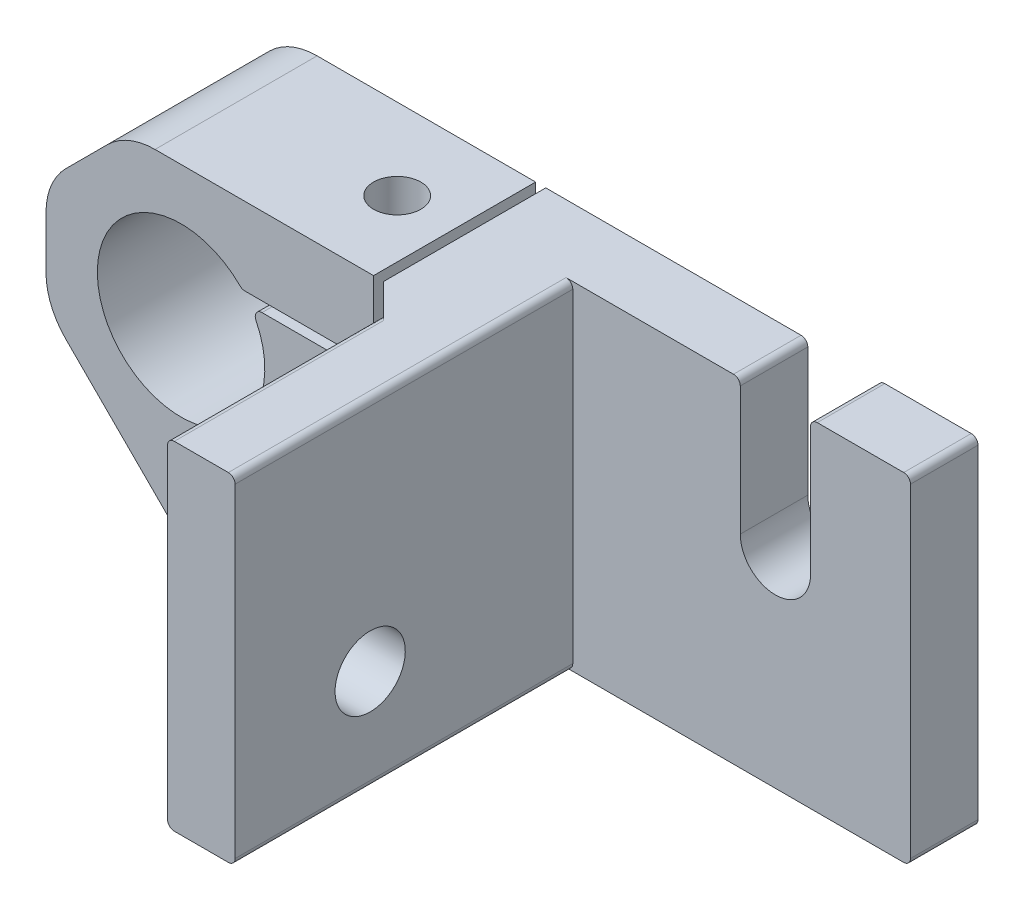
SolidWorks part; units mm, degrees
ref_plane "XY" through (0, 0, 0) normal (0, 0, 1) x (1, 0, 0)
ref_plane "XZ" through (0, 0, 0) normal (0, 1, 0) x (1, 0, 0)
ref_plane "YZ" through (0, 0, 0) normal (1, 0, 0) x (0, 0, -1)
sketch "Sketch1" plane through (0, 0, 0) normal (0, 0, 1) x (1, 0, 0)
  line L0 (-22.5, 12.5) -> (-28.5, 6.5)
  line L1 (-28.5, -12.5) -> (-17.5, -12.5) construction
  line L2 (-28.5, -12.5) -> (-28.5, -1.5) construction
  line L3 (-28.5, 12.5) -> (-5.7, 12.5) construction
  line L4 (28.5, -12.5) -> (28.5, 12.5)
  line L5 (-28.5, -12.5) -> (28.5, 12.5) construction
  line L6 (-28.5, 12.5) -> (28.5, -12.5) construction
  line L7 (28.5, -12.5) -> (-28.5, -12.5) construction
  line L8 (28.5, -12.5) -> (28.5, 12.5) construction
  line L9 (28.5, 12.5) -> (-28.5, 12.5) construction
  line L10 (-28.5, -12.5) -> (-28.5, 12.5) construction
  line L11 (28.5, -12.5) -> (-28.5, 12.5) construction
  line L12 (28.5, 12.5) -> (-28.5, -12.5) construction
  line L13 (-13.9859, 6.75) -> (-4.25, 6.75)
  line L14 (-28.5, 6.5) -> (-28.5, 12.5) construction
  line L15 (-17.5, -12.5) -> (-28.5, -1.5)
  line L16 (-5.7, 12.5) -> (-4.25, 12.5)
  line L17 (-28.5, 6.5) -> (-28.5, 12.5) construction
  line L18 (-28.5, -1.5) -> (-28.5, 6.5)
  line L19 (-17.5, -12.5) -> (28.5, -12.5)
  line L20 (-4.25, 6.75) -> (-4.25, 12.5)
  line L21 (-13.3824, 6) -> (-3.5, 6)
  line L22 (-3.5, 6) -> (-3.5, 12.5)
  line L23 (-13.9859, 6) -> (-3.5, 6) construction
  line L24 (-4.25, 12.5) -> (-3.5, 12.5) construction
  line L25 (-3.5, 12.5) -> (28.5, 12.5)
  line L26 (-22.5, 12.5) -> (-5.7, 12.5)
  arc A0 (-13.9859, 6.75) -> (-13.3824, 6) centre (-18.5, 2.5) ccw
  arc A1 (-13.3824, 6) -> (-13.9859, 6.75) centre (-18.5, 2.5) ccw construction
  point P0 (0, 0)
  point P5 (0, 0)
  dimension "D10" = 18.5
  dimension "D12" = 12.4
  dimension "D1" = 57
  dimension "D2" = 25
  dimension "D3" = 25
  dimension "D4" = 45
  dimension "D5" = 6
  dimension "D6" = 45
  dimension "D7" = 0.75
  dimension "D9" = 11
  dimension "D11" = 2.5
  dimension "D13" = 3.5
  dimension "D14" = 6
extrude "Boss-Extrude1" add sketch "Sketch1" along normal blind 12
sketch "Sketch3" plane through (0, 0, 12) normal (0, 0, 1) x (1, 0, 0)
  line L0 (-17.5, -12.5) -> (28.5, -12.5) construction
  line L1 (28.5, 12.5) -> (3.5, 12.5)
  line L2 (28.5, 12.5) -> (28.5, -12.5)
  line L3 (28.5, -12.5) -> (3.5, -12.5)
  line L4 (3.5, 12.5) -> (3.5, -12.5)
  dimension "D1" = 25
extrude "Cut-Extrude1" cut sketch "Sketch3" against normal blind 7
sketch "Sketch4" plane through (3.5, 0, 0) normal (1, 0, 0) x (0, 0, -1)
  line L0 (0, -12.5) -> (0, 12.5) construction
  line L1 (-12, 12.5) -> (-30, 12.5)
  line L2 (-12, 12.5) -> (-12, -12.5)
  line L3 (-12, -12.5) -> (-30, -12.5)
  line L4 (-30, 12.5) -> (-30, -12.5)
  line L5 (-5, -12.5) -> (-12, -12.5) construction
  circle A0 centre (-20, -5) radius 2.6
  dimension "D2" = 5.2
  dimension "D1" = 30
  dimension "D3" = 5
  dimension "D4" = 20
extrude "Boss-Extrude2" add sketch "Sketch4" against normal blind 5
chamfer "Chamfer1" distance 2 angle 45 1 edges
sketch "Sketch5" plane through (0, 0, 5) normal (0, 0, 1) x (1, 0, 0)
  line L0 (15.9, 2.5) -> (15.9, 12.5)
  line L1 (28.5, 12.5) -> (3.5, 12.5) construction
  line L2 (15.9, 12.5) -> (21.1, 12.5)
  line L3 (21.1, 12.5) -> (21.1, 2.5)
  arc A0 (15.9, 2.5) -> (21.1, 2.5) centre (18.5, 2.5) ccw
  dimension "D1" = 5.2
  dimension "D2" = 2.5
  dimension "D3" = 18.5
extrude "Cut-Extrude2" cut sketch "Sketch5" against normal blind 5
fillet "Fillet1" radius 5 4 edges at (-17.5, -12.5, 6) (-28.5, -1.5, 6) (-28.5, 6.5, 6) (-22.5, 12.5, 6)
fillet "Fillet2" radius 0.5 10 edges at (-13.9859, 6.75, 6) (-13.3824, 6, 6) (28.5, 12.5, 2.5) (28.5, -12.5, 2.5) (3.5, -12.5, 17.5) (3.5, 12.5, 17.5) (15.9, 12.5, 2.5) (21.1, 12.5, 2.5)
ref_plane "Plane1" through (0, 0, 6) normal (0, 0, -1) x (-1, 0, 0)
sketch "Sketch6" plane through (0, 0, 6) normal (0, 0, -1) x (-1, 0, 0)
  line L0 (8.5, 12.5) -> (8.5, -12.5) construction
  line L1 (4.25, 12.5) -> (20.4289, 12.5) construction
  line L2 (15.4289, -12.5) -> (-28, -12.5) construction
  line L3 (8.5, 12.5) -> (10.25, 12.5)
  line L4 (10.25, 12.5) -> (10.25, -7.5)
  line L5 (10.25, -7.5) -> (10.85, -7.5)
  line L6 (10.85, -7.5) -> (10.85, -12)
  line L7 (10.85, -12) -> (11, -12)
  line L8 (11, -12) -> (11, -12.5)
  line L9 (11, -12.5) -> (8.5, -12.5)
  line L10 (8.5, -12.5) -> (8.5, 12.5)
  dimension "D1" = 8.5
  dimension "D2" = 1.75
  dimension "D3" = 2.5
  dimension "D4" = 0.15
  dimension "D5" = 0.5
  dimension "D6" = 5
revolve "Cut-Revolve1" cut sketch "Sketch6" angle 360 about L0
